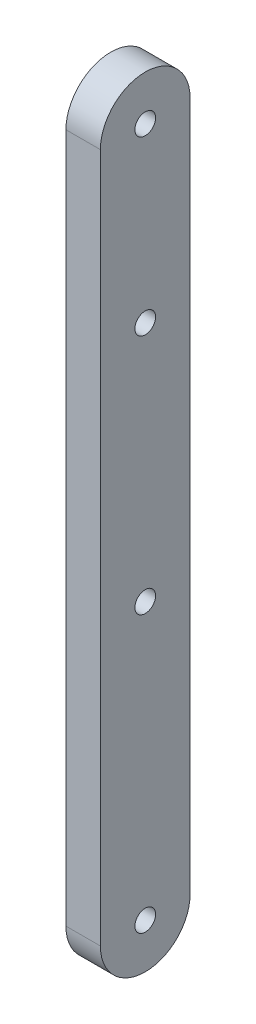
SolidWorks part; units mm, degrees
ref_plane "Front" through (0, 0, 0) normal (0, 0, 1) x (1, 0, 0)
ref_plane "Top" through (0, 0, 0) normal (0, 1, 0) x (1, 0, 0)
ref_plane "Right" through (0, 0, 0) normal (1, 0, 0) x (0, 0, -1)
sketch "Sketch1" plane through (0, 0, 0) normal (1, 0, 0) x (0, 0, -1)
  line L0 (0, 50) -> (0, -50) construction
  line L1 (-6.5, 50) -> (-6.5, -50)
  line L2 (6.5, 50) -> (6.5, -50)
  circle A0 centre (0, 50) radius 1.5
  arc A1 (-6.5, 50) -> (6.5, 50) centre (0, 50) cw
  arc A2 (6.5, -50) -> (-6.5, -50) centre (0, -50) cw
  circle A3 centre (0, 25) radius 1.5
  circle A4 centre (0, -50) radius 1.5
  circle A5 centre (0, -10) radius 1.5
  point P3 (0, 0)
  point P13 (0, 0)
  point P14 (0, 0)
  point P16 (0, 0)
  dimension "D3" = 5
  dimension "D4" = 3
  dimension "D1" = 60
  dimension "D2" = 100
  dimension "D6" = 75
extrude "Boss-Extrude1" add sketch "Sketch1" along normal blind 5
